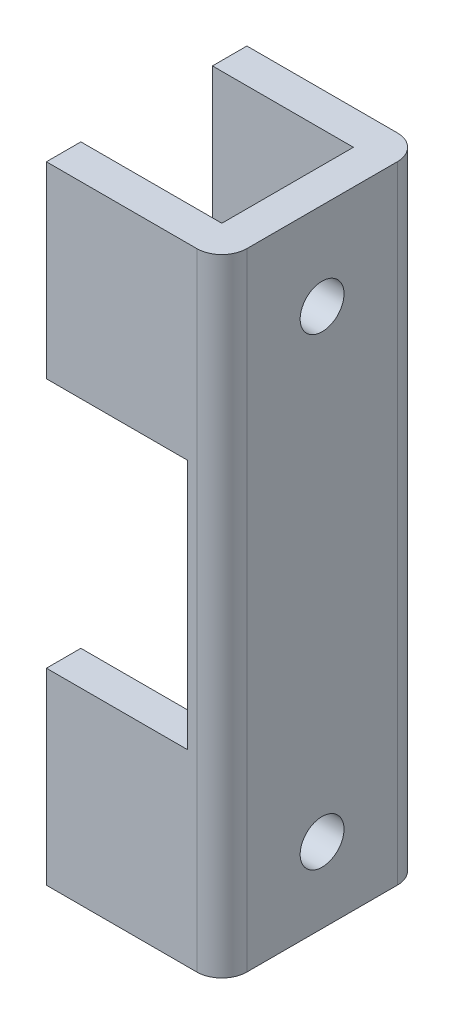
SolidWorks part; units mm, degrees
ref_plane "前视基准面" through (0, 0, 0) normal (0, 0, 1) x (1, 0, 0)
ref_plane "上视基准面" through (0, 0, 0) normal (0, 1, 0) x (1, 0, 0)
ref_plane "右视基准面" through (0, 0, 0) normal (1, 0, 0) x (0, 0, -1)
sketch "草图1" plane through (0, 0, 0) normal (0, 1, 0) x (1, 0, 0)
  line L0 (-8.9538, 10.5077) -> (-8.9538, -5.4923)
  line L1 (-8.9538, -5.4923) -> (3.0462, -5.4923)
  line L2 (-8.9538, 10.5077) -> (3.0462, 10.5077)
  line L3 (5.0462, 8.5077) -> (5.0462, -3.4923)
  arc A0 (3.0462, 10.5077) -> (5.0462, 8.5077) centre (3.0462, 8.5077) cw
  arc A1 (3.0462, -5.4923) -> (5.0462, -3.4923) centre (3.0462, -3.4923) ccw
  point P10 (5.0462, -5.4923)
  dimension "D3" = 2
  dimension "D4" = 2
  dimension "D1" = 16
  dimension "D2" = 14
extrude "凸台-拉伸1" add sketch "草图1" along normal blind 50
sketch "草图2" plane through (0, 50, 0) normal (0, 1, 0) x (1, 0, 0)
  line L12 (2.2962, 7.7577) -> (-6.2038, 7.7577)
  line L13 (-6.2038, 7.7577) -> (-6.2038, -2.7423)
  line L14 (-6.2038, -2.7423) -> (2.2962, -2.7423)
  line L15 (2.2962, -2.7423) -> (2.2962, 7.7577)
  line L16 (2.2962, 7.7577) -> (-6.2038, 7.7577)
  line L17 (-6.2038, 7.7577) -> (-6.2038, -2.7423)
  line L18 (-6.2038, -2.7423) -> (2.2962, -2.7423)
  line L19 (2.2962, -2.7423) -> (2.2962, 7.7577)
  dimension "D1" = 2.75
extrude "切除-拉伸1" cut sketch "草图2" against normal through all
sketch "草图3" plane through (0, 50, 0) normal (0, 1, 0) x (1, 0, 0)
  line L0 (-6.2038, 7.7577) -> (-8.9538, 7.7577)
  line L1 (-8.9538, 10.5077) -> (-8.9538, -5.4923) construction
  line L2 (-8.9538, 7.7577) -> (-8.9538, -2.7423)
  line L3 (-8.9538, -2.7423) -> (-6.2038, -2.7423)
  line L4 (-6.2038, -2.7423) -> (-6.2038, 7.7577)
extrude "切除-拉伸2" cut sketch "草图3" against normal through all
sketch "草图4" plane through (5.0462, 0, 0) normal (1, 0, 0) x (0, 0, -1)
  line L0 (-3.4923, 50) -> (-3.4923, 0) construction
  line L1 (-3.4923, 50) -> (8.5077, 50) construction
  circle A0 centre (2.5077, 43) radius 1.75
  circle A1 centre (2.5077, 6) radius 1.75
  dimension "D1" = 6
  dimension "D5" = 3.5
  dimension "D6" = 3.5
  dimension "D2" = 7
  dimension "D3" = 37
  dimension "D4" = 6
extrude "切除-拉伸3" cut sketch "草图4" against normal through all
sketch "草图6" plane through (0, 0, -10.5077) normal (0, 0, -1) x (-1, 0, 0)
  line L0 (8.9538, 35) -> (8.9538, 15)
  line L1 (8.9538, 50) -> (8.9538, 0) construction
  line L2 (8.9538, 15) -> (-2.2962, 15)
  line L3 (-2.2962, 15) -> (-2.2962, 35)
  line L4 (-2.2962, 35) -> (8.9538, 35)
  line L5 (-3.0462, 50) -> (8.9538, 50) construction
  dimension "D1" = 20
  dimension "D2" = 11.25
  dimension "D3" = 15
extrude "切除-拉伸4" cut sketch "草图6" against normal through all
